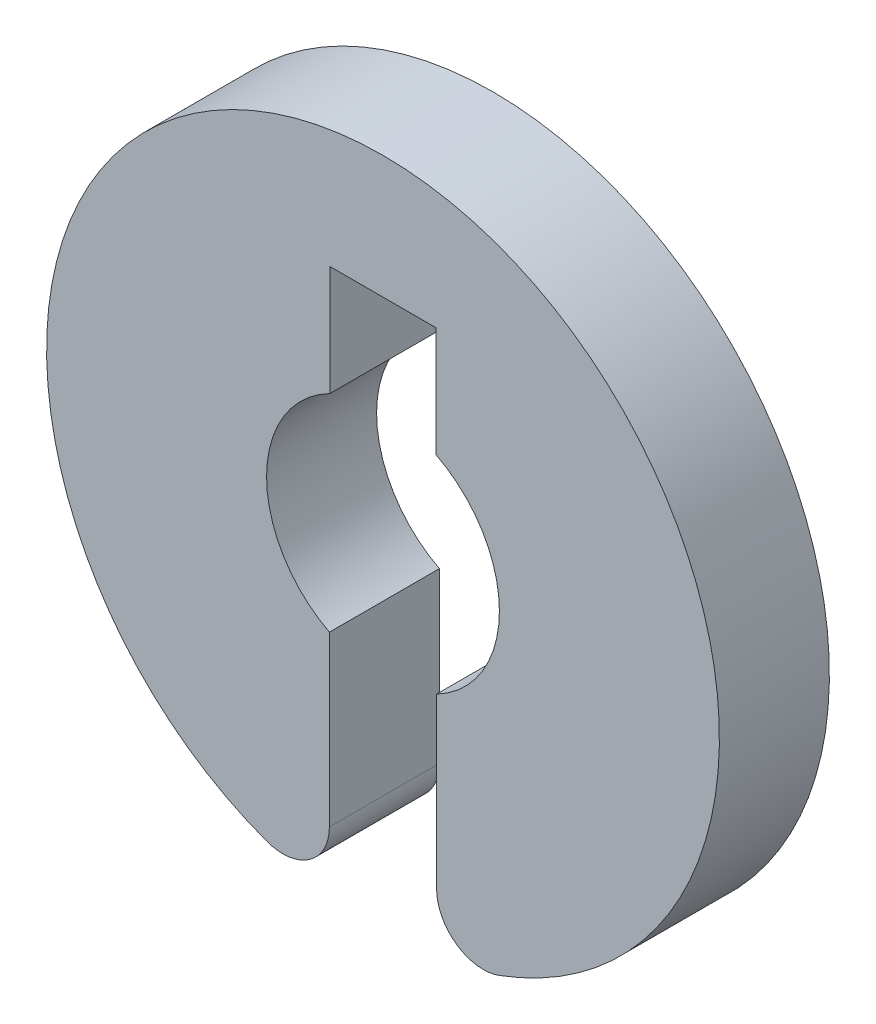
SolidWorks part; units mm, degrees
material "Acrylic (Medium-high impact)"
ref_plane "Front Plane" through (0, 0, 0) normal (0, 0, 1) x (1, 0, 0)
ref_plane "Top Plane" through (0, 0, 0) normal (0, 1, 0) x (1, 0, 0)
ref_plane "Right Plane" through (0, 0, 0) normal (1, 0, 0) x (0, 0, -1)
sketch "스케치1" plane through (0, 0, 0) normal (0, 0, 1) x (1, 0, 0)
  line L0 (0, 10.85) -> (0, 0) construction
  line L6 (-1.4475, 5.8258) -> (1.4475, 5.8258)
  line L7 (0, 0) -> (0, -5.9379) construction
  line L8 (-1.4625, -9.0577) -> (1.4625, -9.0577) construction
  line L9 (-1.4625, -9.0577) -> (-1.4625, -2.8181)
  line L10 (-1.4625, -2.8181) -> (1.4625, -2.8181) construction
  line L11 (1.4625, -9.0577) -> (1.4625, -2.8181)
  line L12 (-1.4625, -9.0577) -> (1.4625, -2.8181) construction
  line L13 (-1.4625, -2.8181) -> (1.4625, -9.0577) construction
  line L14 (-1.4475, 5.8258) -> (-1.4475, 2.8258)
  line L15 (-1.4475, 2.8258) -> (1.4475, 2.8258) construction
  line L16 (1.4475, 5.8258) -> (1.4475, 2.8258)
  line L17 (-1.4475, 5.8258) -> (1.4475, 2.8258) construction
  line L18 (-1.4475, 2.8258) -> (1.4475, 5.8258) construction
  circle A0 centre (0, 0) radius 9.175 construction
  circle A1 centre (0, 0) radius 3.175 construction
  arc A2 (-1.4625, -9.0577) -> (1.4625, -9.0577) centre (0, 0) cw
  arc A3 (1.4625, -2.8181) -> (1.4475, 2.8258) centre (0, 0) ccw
  arc A4 (-1.4475, 2.8258) -> (-1.4625, -2.8181) centre (0, 0) ccw
  point P2 (0, 10.85)
  point P5 (0, 4.3258)
  point P10 (0, -5.9379)
  dimension "D1" = 6
  dimension "D2" = 6.35
  dimension "D3" = 2.895
  dimension "D4" = 3
  dimension "D5" = 2.925
extrude "보스-돌출1" add sketch "스케치1" along normal blind 3
fillet "필렛1" radius 1.27 2 edges at (-1.4625, -9.0577, 1.5) (1.4625, -9.0577, 1.5)
